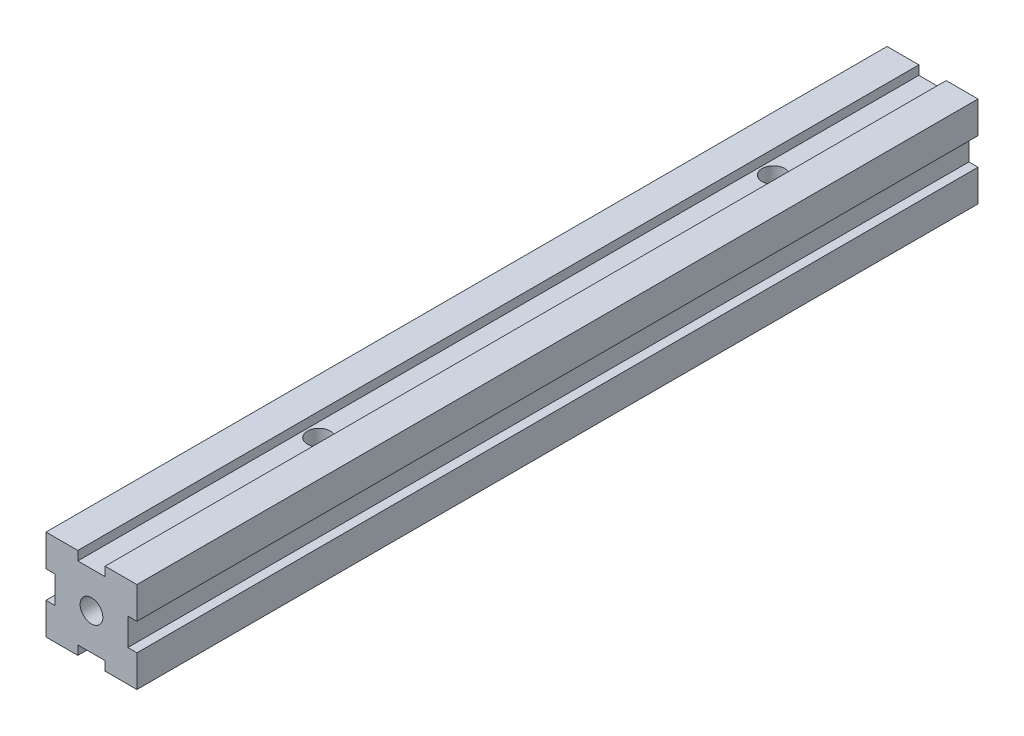
SolidWorks part; units mm, degrees
ref_plane "前视基准面" through (0, 0, 0) normal (0, 0, 1) x (1, 0, 0)
ref_plane "上视基准面" through (0, 0, 0) normal (0, 1, 0) x (1, 0, 0)
ref_plane "右视基准面" through (0, 0, 0) normal (1, 0, 0) x (0, 0, -1)
sketch "草图1" plane through (0, 0, 0) normal (0, 0, 1) x (1, 0, 0)
  line L0 (0, -13) -> (0, -20)
  line L1 (0, 0) -> (7, 0)
  line L2 (0, 0) -> (0, -7)
  line L3 (0, -20) -> (7, -20)
  line L4 (20, 0) -> (20, -7)
  line L5 (20, -7) -> (18, -7)
  line L6 (13, -20) -> (20, -20)
  line L7 (20, -13) -> (18, -13)
  line L8 (18, -7) -> (18, -13)
  line L9 (0, -7) -> (2, -7)
  line L10 (13, 0) -> (20, 0)
  line L11 (0, -13) -> (2, -13)
  line L12 (2, -7) -> (2, -13)
  line L13 (20, -13) -> (20, -20)
  line L14 (7, 0) -> (7, -2)
  line L15 (7, -2) -> (13, -2)
  line L16 (13, 0) -> (13, -2)
  line L17 (0, -7) -> (0, -13) construction
  line L18 (7, -20) -> (7, -18)
  line L19 (7, -18) -> (13, -18)
  line L20 (13, -20) -> (13, -18)
  line L21 (7, 0) -> (13, 0) construction
  line L22 (20, -7) -> (20, -13) construction
  line L23 (13, -20) -> (7, -20) construction
  line L24 (2, -10) -> (18, -10) construction
  line L25 (10, -2) -> (10, -18) construction
  circle A0 centre (10, -10) radius 2.5
  point P21 (10, 0)
  point P22 (10, -2)
  point P23 (10, -18)
  point P24 (2, -10)
  point P25 (18, -10)
  point P26 (0, -10)
  dimension "D13" = 5
  dimension "D1" = 20
  dimension "D2" = 20
  dimension "D3" = 6
  dimension "D4" = 6
  dimension "D5" = 6
  dimension "D6" = 6
  dimension "D7" = 10
  dimension "D8" = 10
  dimension "D9" = 2
  dimension "D10" = 2
  dimension "D11" = 2
  dimension "D12" = 2
extrude "凸台-拉伸1" add sketch "草图1" along normal blind 185
sketch "草图2" plane through (0, 0, 0) normal (0, 1, 0) x (1, 0, 0)
  line L0 (10, 0) -> (10, -185) construction
  line L1 (13, 0) -> (7, 0) construction
  line L2 (13, -185) -> (7, -185) construction
  circle A0 centre (10, -35) radius 2.5
  circle A1 centre (10, -135) radius 2.5
  dimension "D1" = 5
  dimension "D2" = 35
  dimension "D3" = 100
extrude "切除-拉伸1" cut sketch "草图2" against normal through all
